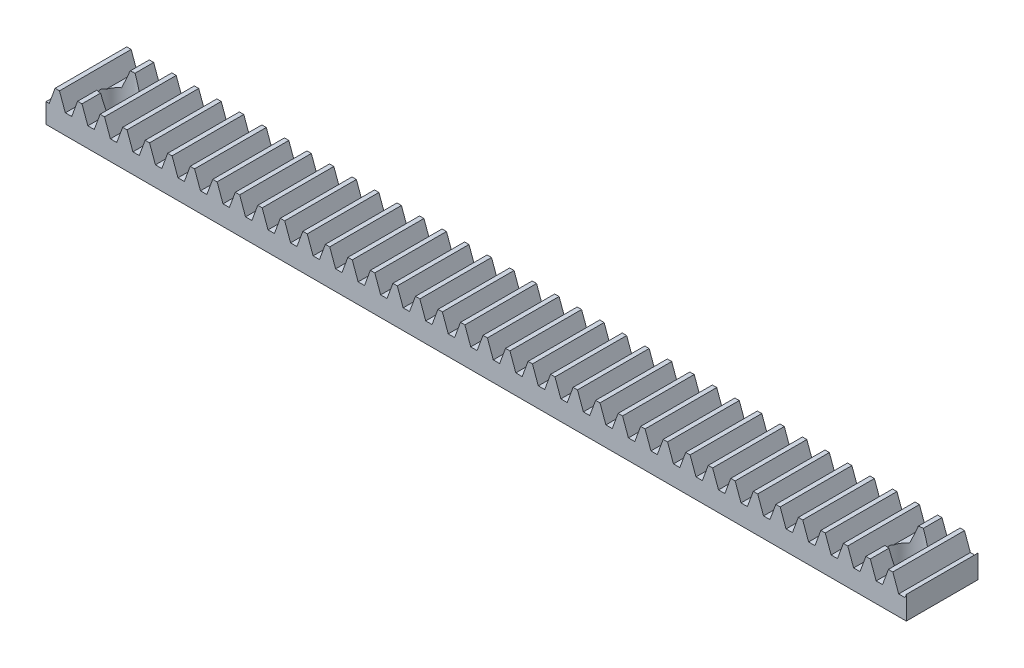
SolidWorks part; units mm, degrees
extrude "Blank" add sketch "BlankSke" against normal blind 5
sketch "BlankSke" plane through (0, 0, 0) normal (0, 0, 1) x (1, 0, 0)
  line L1 (0, 0) -> (60, 0)
  line L2 (0, 0) -> (0, 2.5)
  line L3 (0, 2.5) -> (60, 2.5)
  line L4 (60, 0) -> (60, 2.5)
  dimension "Length" = 60
  dimension "Blank_height" = 2.5
ref_plane "Plane1" through (0, 0, 0) normal (0, 0, 1) x (1, 0, 0)
ref_plane "Plane2" through (0, 0, 0) normal (0, 1, 0) x (1, 0, 0)
ref_plane "Plane3" through (0, 0, 0) normal (1, 0, 0) x (0, 0, -1)
other "Configuration Table"
sketch "HoldingSke" plane through (0, 0, 0) normal (0, 1, 0) x (1, 0, 0)
  line L0 (0, 0) -> (0.2783, 1.9805)
  line L1 (-15, 0) -> (100, 0) construction
  line L2 (0, 0) -> (-2.1039, 2.3779)
  line L3 (0, 0) -> (-11.863, 4.5341)
  line L4 (0, 0) -> (6.6156, 5.5511)
  line L5 (0, 0) -> (-23.7986, -8.8762)
  line L6 (0, 0) -> (-10.5278, -7.1032)
  line L9 (-71.009, 38.7566) -> (-14.6274, 59.2778)
  line L10 (-76.2, 2.8779) -> (-74.2, 2.8779)
  line L11 (0, 0) -> (-5, 0)
  line L12 (-76.2, 101.6) -> (-76.181, 101.6)
  line L13 (24.9733, 27.94) -> (52.9518, 28.4284)
  line L14 (24.9733, 27.94) -> (24.9743, 27.94)
  line L15 (24.9733, 27.94) -> (100.4006, 29.5858)
  circle A0 centre (0, 0) radius 19.05
  circle A1 centre (0, 0) radius 1
  circle A2 centre (0, 0) radius 12.7
  dimension "MPH" = 2
  dimension "Diameter" = 38.1
  dimension "Num_teeth" = 40
  dimension "Pitch" = 2
  dimension "Show_teeth" = 998
  dimension "Thickness" = 12.7
  dimension "Ap" = 20
  dimension "Pitch_height" = 2
  dimension "Width" = 5
  dimension "Backlash" = 0.019
  dimension "Addendum_fac" = 1
  dimension "Dedendum_fac" = 1.25
  dimension "Clearance_fac" = 0.25
  dimension "Dedendum_add" = 0.001
  dimension "Length" = 60
  dimension "Module" = 0.5
sketch "TooCutSkeIll" plane through (0, 0, 0) normal (0, 0, 1) x (1, 0, 0)
  line L0 (-0.6269, 2.4868) -> (-0.2524, 1.4579)
  line L1 (-0.134, 1.375) -> (0.134, 1.375)
  line L2 (0.2524, 1.4579) -> (0.6269, 2.4868)
  line L3 (60, 2.5) -> (0, 2.5) construction
  line L4 (0, 0) -> (0, 64.897) construction
  line L5 (-13.208, 2) -> (12.954, 2) construction
  line L6 (0, 0) -> (60, 0) construction
  line L7 (0.4497, 2) -> (0.4497, 48.7463) construction
  line L8 (-0.4497, 2) -> (-0.4497, 48.7463) construction
  line L9 (0.6457, 2.5) -> (0.6457, 2.5254)
  line L10 (-0.6457, 2.5) -> (-0.6457, 2.5254)
  line L11 (-0.6457, 2.5254) -> (0.6457, 2.5254)
  arc A0 (0.134, 1.375) -> (0.2524, 1.4579) centre (0.134, 1.501) ccw
  arc A1 (-0.2524, 1.4579) -> (-0.134, 1.375) centre (-0.134, 1.501) ccw
  arc A2 (0.6457, 2.5) -> (0.6269, 2.4868) centre (0.6457, 2.48) ccw
  arc A3 (-0.6269, 2.4868) -> (-0.6457, 2.5) centre (-0.6457, 2.48) ccw
  dimension "Pitch_height" = 2
  dimension "Addendum_plus" = 0.5254
  dimension "Pressure_angle" = 20
  dimension "Gap_width" = 0.8994
  dimension "Dedendum" = 0.625
extrude "ToothCutIll" [suppressed] cut sketch "TooCutSkeIll" against normal through all
sketch "TooCutSkeSim" plane through (0, 0, 0) normal (0, 0, 1) x (1, 0, 0)
  line L0 (0.2222, 1.375) -> (-0.2222, 1.375)
  line L1 (0.6409, 2.5254) -> (0.2222, 1.375)
  line L2 (0, 17.4625) -> (0, 53.467) construction
  line L3 (0.6409, 2.5254) -> (-0.6409, 2.5254)
  line L6 (-0.6409, 2.5254) -> (-0.2222, 1.375)
  line L9 (-0.4497, 2) -> (0.4497, 2) construction
  line L10 (0, 0) -> (60, 0) construction
  line L11 (0.4497, 2) -> (0.4497, 53.467) construction
  line L12 (-0.4497, 2) -> (-0.4497, 53.467) construction
  dimension "Pitch_height" = 2
  dimension "Addendum_plus" = 0.5254
  dimension "Pressure_angle" = 20
  dimension "Gap_width" = 0.8994
  dimension "Dedendum" = 0.625
extrude "ToothCutSim" cut sketch "TooCutSkeSim" against normal through all
pattern_linear "TeethCuts" count 39 spacing 1.5708 along (1, 0, 0) of "ToothCutIll", "ToothCutSim"
sketch "Sketch1" plane through (0, 0, 0) normal (0, -1, 0) x (1, 0, 0)
  circle A0 centre (2.5, -2.5) radius 1.2
  circle A1 centre (57.5, -2.5) radius 1.2
extrude "Cut-Extrude1" cut sketch "Sketch1" against normal blind 10
equation "' \"Module@HoldingSke\" = 6.35"
equation "' \"Num_teeth@HoldingSke\" = 12"
equation "' \"Ap@HoldingSke\" =  20"
equation "' \"Ap@HoldingSke\" = 20"
equation "' \"Width@HoldingSke\" = 0.25 * 25.4"
equation "' \"Show_teeth@HoldingSke\" = 500"
equation "' \"Backlash@HoldingSke\" = 0.009 * 25.4"
equation "' \"Addendum_fac@HoldingSke\" = 1.0"
equation "' \"Dedendum_fac@HoldingSke\" = 1.25"
equation "' \"Dedendum_add@HoldingSke\" = 0.00005 * 25.4"
equation "' \"Clearance_fac@HoldingSke\" = 0.25"
equation "' \"Pitch_height@HoldingSke\" = 1 * 25.4"
equation "' \"Length@HoldingSke\" = 4.71 * 25.4"
equation "\"Pitch@HoldingSke\" = 1 / \"Module@HoldingSke\""
equation "\"MPH@HoldingSke\" = \"Dedendum_fac@HoldingSke\" / \"Pitch@HoldingSke\" + 2 * \"Dedendum_add@HoldingSke\" + 0.002 * 25.4"
equation "\"MPH@HoldingSke\" = ((sgn( \"MPH@HoldingSke\" - \"Pitch_height@HoldingSke\")+1)*( \"MPH@HoldingSke\" - \"Pitch_height@HoldingSke\"))/2 + \"Pitch_height@HoldingSke\""
equation "\"Blank_height@BlankSke\" = \"Pitch_height@HoldingSke\" + \"Addendum_fac@HoldingSke\"  / \"Pitch@HoldingSke\" "
equation "\"Length@BlankSke\" =  \"Length@HoldingSke\""
equation "\"Face_width@Blank\" = \"Width@HoldingSke\""
equation "\"Pressure_angle@TooCutSkeIll\" = \"Ap@HoldingSke\""
equation "\"Addendum_plus@TooCutSkeIll\" =  \"Addendum_fac@HoldingSke\"  / \"Pitch@HoldingSke\" + 0.001 *25.4"
equation "\"Dedendum@TooCutSkeIll\" = \"Dedendum_fac@HoldingSke\"  / \"Pitch@HoldingSke\""
equation "\"Pitch_height@TooCutSkeIll\" =  \"MPH@HoldingSke\""
equation "\"Gap_width@TooCutSkeIll\" = 3.14159265 / 2 / \"Pitch@HoldingSke\" + 6 * \"Backlash@HoldingSke\""
equation "\"Pressure_angle@TooCutSkeSim\" = \"Ap@HoldingSke\""
equation "\"Addendum_plus@TooCutSkeSim\" =  \"Addendum_fac@HoldingSke\"  / \"Pitch@HoldingSke\" + 0.001 * 25.4"
equation "\"Dedendum@TooCutSkeSim\" = \"Dedendum_fac@HoldingSke\"  / \"Pitch@HoldingSke\""
equation "\"Pitch_height@TooCutSkeSim\" =  \"MPH@HoldingSke\""
equation "\"Gap_width@TooCutSkeSim\" = 3.14159265 / 2 / \"Pitch@HoldingSke\" + 6 * \"Backlash@HoldingSke\""
equation "\"Root_fillet@TooCutSkeIll\" = \"Clearance_fac@HoldingSke\" / \"Pitch@HoldingSke\" + \"Dedendum_add@HoldingSke\""
equation "\"Break_rad@TooCutSkeIll\" = 0.02 / \"Pitch@HoldingSke\" * 2"
equation "\"Linear_pitch@TeethCuts\" = 3.14159265 / \"Pitch@HoldingSke\""
equation "\"Num_teeth@HoldingSke\" = int( ( \"Length@HoldingSke\" + 0 ) / (3.14159265 / \"Pitch@HoldingSke\")) + 0.9999  + 1"
equation " \"Num_teeth@TeethCuts\" = int( \"Show_teeth@HoldingSke\" ) + 1"
equation " \"Num_teeth@TeethCuts\" = ((sgn( \"Num_teeth@TeethCuts\" - \"Num_teeth@HoldingSke\" )-1)*( \"Num_teeth@TeethCuts\" - \"Num_teeth@HoldingSke\" ))/-2+ \"Num_teeth@HoldingSke\""
equation " \"Num_teeth@TeethCuts\" = ((sgn( \"Num_teeth@TeethCuts\" - 2.0)+1)*( \"Num_teeth@TeethCuts\" - 2.0))/2 +2.0"
